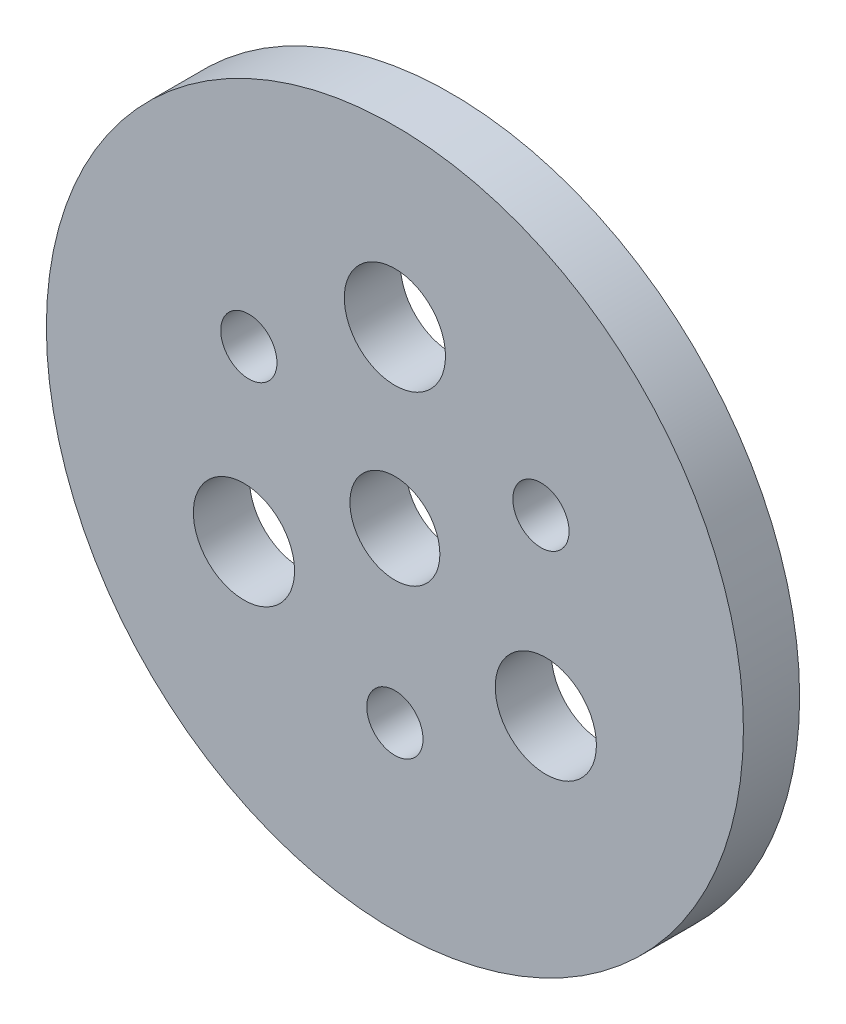
SolidWorks part; units mm, degrees
ref_plane "Front Plane" through (0, 0, 0) normal (0, 0, 1) x (1, 0, 0)
ref_plane "Top Plane" through (0, 0, 0) normal (0, 1, 0) x (1, 0, 0)
ref_plane "Right Plane" through (0, 0, 0) normal (1, 0, 0) x (0, 0, -1)
sketch "Sketch1" plane through (0, 0, 0) normal (0, 0, 1) x (1, 0, 0)
  line L0 (0, 0) -> (0, -15) construction
  line L1 (0, 0) -> (0, 15.5) construction
  circle A0 centre (0, 0) radius 31
  circle A1 centre (0, 0) radius 4
  circle A2 centre (0, -15) radius 2.5
  circle A3 centre (-12.9904, 7.5) radius 2.5
  circle A4 centre (12.9904, 7.5) radius 2.5
  circle A5 centre (0, 15.5) radius 4.5
  circle A6 centre (13.4234, -7.75) radius 4.5
  circle A7 centre (-13.4234, -7.75) radius 4.5
  dimension "D1" = 62
  dimension "D2" = 8
  dimension "D4" = 5
  dimension "D7" = 9
  dimension "D3" = 15
  dimension "D6" = 15.5
  dimension "D5" = 3
  dimension "D8" = 3
extrude "Boss-Extrude1" add sketch "Sketch1" along normal blind 5
